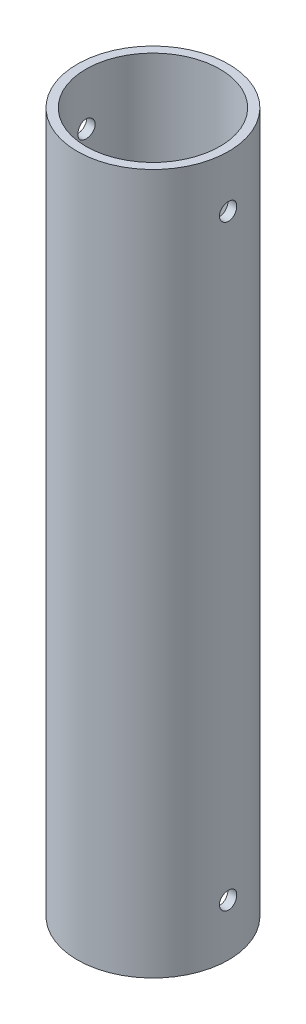
SolidWorks part; units mm, degrees
ref_plane "Plan de face" through (0, 0, 0) normal (0, 0, 1) x (1, 0, 0)
ref_plane "Plan de dessus" through (0, 0, 0) normal (0, 1, 0) x (1, 0, 0)
ref_plane "Plan de droite" through (0, 0, 0) normal (1, 0, 0) x (0, 0, -1)
sketch "Esquisse1" plane through (0, 0, 0) normal (0, 1, 0) x (1, 0, 0)
  circle A0 centre (0, 0) radius 15.5
  circle A1 centre (0, 0) radius 17.5
  dimension "D1" = 35
  dimension "D2" = 2
extrude "Boss.-Extru.1" add sketch "Esquisse1" along normal blind 162
sketch "Esquisse2" plane through (0, 0, 0) normal (1, 0, 0) x (0, 0, -1)
  line L0 (17.5, 162) -> (-17.5, 162) construction
  line L1 (-17.5, 0) -> (17.5, 0) construction
  circle A0 centre (0, 150) radius 2
  circle A1 centre (0, 12) radius 2
  dimension "D3" = 4
  dimension "D4" = 4
  dimension "D1" = 12
  dimension "D2" = 12
extrude "Enlèv. mat.-Extru.1" cut sketch "Esquisse2" against normal through all both and the other way through all
